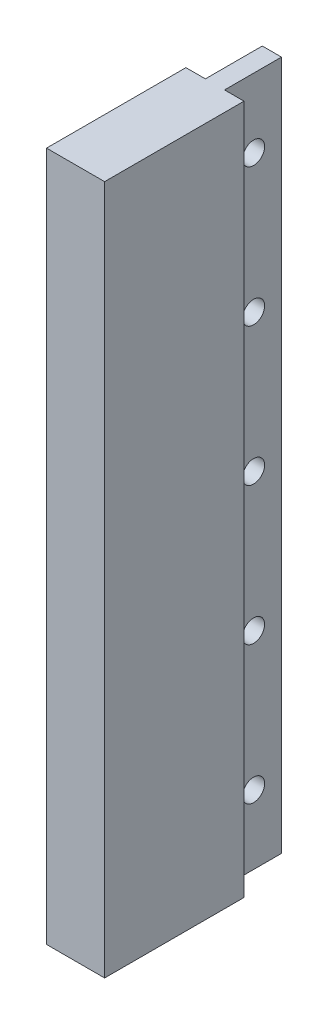
SolidWorks part; units mm, degrees
ref_plane "Front Plane" through (0, 0, 0) normal (1, 0, 0) x (0, 1, 0)
ref_plane "Top Plane" through (0, 0, 0) normal (0, 0, 1) x (0, 1, 0)
ref_plane "Right Plane" through (0, 0, 0) normal (0, 1, 0) x (-1, 0, 0)
sketch "Sketch1" plane through (0, 0, 0) normal (1, 0, 0) x (0, 1, 0)
  line L1 (0, 0) -> (118.75, 0)
  line L2 (0, 0) -> (0, 24)
  line L3 (0, 24) -> (118.75, 24)
  line L4 (118.75, 0) -> (118.75, 24)
  dimension "D1" = 118.75
  dimension "D2" = 24
extrude "Boss-Extrude1" add sketch "Sketch1" against normal blind 10
sketch "Sketch2" plane through (0, 0, 0) normal (0, -1, 0) x (1, 0, 0)
  line L1 (-10, 0) -> (-6.65, 0)
  line L2 (-10, 0) -> (-10, -9.8)
  line L3 (-10, -9.8) -> (-6.65, -9.8)
  line L4 (-6.65, 0) -> (-6.65, -9.8)
  line L5 (0, 0) -> (-3.35, 0)
  line L6 (0, 0) -> (0, -9.8)
  line L7 (0, -9.8) -> (-3.35, -9.8)
  line L8 (-3.35, 0) -> (-3.35, -9.8)
  line L9 (-6.65, -9.8) -> (-3.35, -9.8)
  line L10 (-6.65, -9.8) -> (-6.65, 0)
  line L11 (-6.65, 0) -> (-3.35, 0)
  line L12 (-3.35, -9.8) -> (-3.35, 0)
  line M12 (-10, 0) -> (0, 0)
  dimension "D1" = 9.8
  dimension "D2" = 3.35
  dimension "D3" = 3.35
extrude "Boss-Extrude2" add sketch "Sketch2" against normal through all contours L4 L9 L8 M12
sketch "Sketch3" plane through (0, 0, 0) normal (0, -1, 0) x (1, 0, 0)
  line L0 (-3.35, 20.65) -> (-3.35, 3.35)
  line L1 (0, 24) -> (-10, 24)
  line L2 (0, 24) -> (0, 0)
  line L3 (0, 0) -> (-10, 0)
  line L4 (-10, 24) -> (-10, 0)
  line L5 (-3.35, 3.35) -> (-6.65, 3.35)
  line L6 (-6.65, 20.65) -> (-6.65, 3.35)
  line L7 (-3.35, 20.65) -> (-6.65, 20.65)
  line L9 (-6.65, 20.65) -> (-3.35, 20.65)
  line L10 (-6.65, 20.65) -> (-6.65, 24)
  line L11 (-6.65, 24) -> (-3.35, 24)
  line L12 (-3.35, 20.65) -> (-3.35, 24)
  line L13 (-6.65, 3.35) -> (-3.35, 3.35)
  line L14 (-6.65, 3.35) -> (-6.65, -9.8)
  line L15 (-6.65, -9.8) -> (-3.35, -9.8)
  line L16 (-3.35, 3.35) -> (-3.35, -9.8)
  line M13 (-6.65, 0) -> (-6.65, -9.8)
  line M14 (-6.65, -9.8) -> (-3.35, -9.8)
  line M15 (-3.35, -9.8) -> (-3.35, 0)
  dimension "D1" = 3.35
extrude "Boss-Extrude3" [suppressed] add sketch "Sketch3" along normal blind 4.9 contours L7 L12 L1 L10 | L0 L7 L6 L5 | L16 L5 L14 L3 | L3 M15 M13 M14
sketch "Sketch4" plane through (-6.65, 0, 0) normal (-1, 0, 0) x (0, -1, 0)
  line L1 (-106.875, 0) -> (-118.75, 0)
  line L2 (-106.875, 0) -> (-106.875, -5)
  line L3 (-106.875, -5) -> (-118.75, -5)
  line L4 (-118.75, 0) -> (-118.75, -5)
  circle A0 centre (-106.875, -5) radius 1.9
  dimension "D2" = 3.8
  dimension "D1" = 5
  dimension "D3" = 11.875
extrude "Cut-Extrude1" cut sketch "Sketch4" against normal up to next contours A0
sketch "Sketch5" plane through (0, 118.75, 0) normal (0, 1, 0) x (-1, 0, 0)
  line L0 (3.25, 20.75) -> (3.25, 3.25)
  line L1 (0, 24) -> (10, 24)
  line L2 (0, 24) -> (0, 0)
  line L3 (0, 0) -> (10, 0)
  line L4 (10, 24) -> (10, 0)
  line L5 (3.25, 3.25) -> (6.75, 3.25)
  line L6 (6.75, 20.75) -> (6.75, 3.25)
  line L7 (3.25, 20.75) -> (6.75, 20.75)
  line L9 (3.25, 20.75) -> (6.75, 20.75)
  line L10 (3.25, 20.75) -> (3.25, 24)
  line L11 (3.25, 24) -> (6.75, 24)
  line L12 (6.75, 20.75) -> (6.75, 24)
  dimension "D1" = 3.25
extrude "Cut-Extrude2" [suppressed] cut sketch "Sketch5" against normal blind 5 contours L10 L9 L12 L11 | L0 L5 L6 L7
ref_plane "Plane1" through (0, 59.375, 0) normal (0, -1, 0) x (-1, 0, 0)
mirror "Mirror1" [suppressed] about plane through (0, 59.375, 0) normal (0, -1, 0)
pattern_linear "LPattern1" count 5 spacing 23.75 along (0, -1, 0) of "Cut-Extrude1"
equation "\"whitekey_cutout_length\"= 101.5"
equation "\"key_mount_recess_length\"=50"
equation "\"key_mount_recess_height\"=12.5"
equation "\"key_mount_recess_depth\"=1.5"
equation "\"wall_thickness\"=10"
equation "\"guide_brace_height\"=20"
equation "\"guide_brace_thickness\"=2"
equation "\"dowel_recess_depth\"=10"
equation "\"dowel_recess_offset\"=3.25"
equation "\"base_mount_height\"=40"
equation "\"base_rear_length\"=80"
equation "\"base_front_length\"=111.5"
equation "\"screw_hole_wall_offset\"=7.25"
equation "\"screw_hole_edge_inset\"=\"dowel_recess_depth\"/2"
equation "\"screw_hole_diameter\"=3.8"
equation "\"screw_head_hole_diameter\"=6.7"
equation "\"screw_nut_hole_side_len\"=3.5"
equation "\"screw_shaft_diameter\"=3.5"
equation "\"switch_board_width\"=30"
equation "\"switch_board_wall_offset\"=11.5"
equation "\"heatset_insert_hole_diameter\"=4.8"
equation "\"heatset_insert_hole_depth\"=3.8"
equation "\"D1@Boss-Extrude1\"=\"wall_thickness\""
equation "\"D2@Sketch2\"=\"dowel_recess_offset\"+\"dowel_insert_tolerance\""
equation "\"D3@Sketch2\"=\"dowel_recess_offset\"+\"dowel_insert_tolerance\""
equation "\"D1@Boss-Extrude3\"=\"front_rear_panel_recess_depth\"-\"dowel_insert_tolerance\""
equation "\"D1@Sketch3\"=\"dowel_recess_offset\"+\"dowel_insert_tolerance\""
equation "\"D1@Sketch2\"=\"dowel_recess_depth\"-\"dowel_insert_tolerance\"*2"
equation "\"D1@Sketch4\"=\"screw_hole_edge_inset\""
equation "\"D2@Sketch4\"=\"screw_hole_diameter\""
equation "\"D1@Sketch5\"=\"dowel_recess_offset\""
equation "\"D1@Cut-Extrude2\"=\"front_rear_panel_recess_depth\""
equation "\"screw_nut_recess_offset\"=0.35"
equation "\"screw_head_and_nut_recess_depth\"=2.5"
equation "\"front_rear_panel_width\"=23.75"
equation "\"rod_length_adj\"=0.5"
equation "\"rod_insert_length\"=2.8"
equation "\"D1@Sketch1\"=\"front_rear_panel_width\"*5"
equation "\"switch_board_thickness\"=1.6"
equation "\"front_panel_height\"=24"
equation "\"rod_diameter\"=5"
equation "\"rod_head_diameter\"=8"
equation "\"switch_black_key_mount_height\"=8"
equation "\"switch_white_key_mount_height\"=3"
equation "\"D2@Sketch1\"=\"front_panel_height\""
equation "\"dowel_insert_tolerance\"=0.1"
equation "\"front_rear_panel_recess_depth\"=5"
equation "\"D3@Sketch4\"=\"front_rear_panel_width\"/2"
equation "\"D3@LPattern1\"=\"front_rear_panel_width\""
